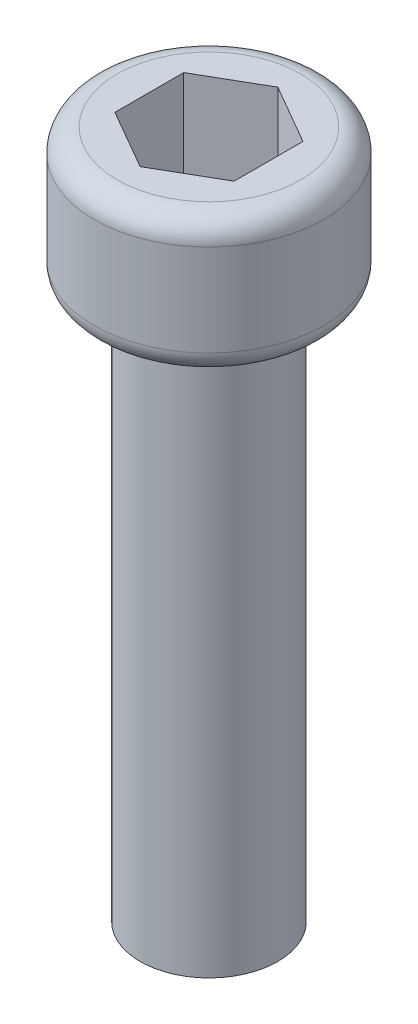
SolidWorks part; units mm, degrees
material "AISI 304"
ref_plane "前视基准面" through (0, 0, 0) normal (0, 0, 1) x (1, 0, 0)
ref_plane "上视基准面" through (0, 0, 0) normal (0, 1, 0) x (1, 0, 0)
ref_plane "右视基准面" through (0, 0, 0) normal (1, 0, 0) x (0, 0, -1)
sketch "草图1" plane through (0, 0, 0) normal (0, 1, 0) x (1, 0, 0)
  circle A0 centre (0, 0) radius 2.5
  dimension "D1" = 5
extrude "凸台-拉伸1" add sketch "草图1" along normal blind 3
sketch "草图2" plane through (0, 3, 0) normal (0, 1, 0) x (1, 0, 0)
  line L0 (0, 2.717) -> (0, -3.1539) construction
  line L2 (0, 1.5) -> (-1.299, 0.75)
  line L3 (-1.299, 0.75) -> (-1.299, -0.75)
  line L4 (-1.299, -0.75) -> (0, -1.5)
  line L5 (0, -1.5) -> (1.299, -0.75)
  line L6 (1.299, -0.75) -> (1.299, 0.75)
  line L7 (1.299, 0.75) -> (0, 1.5)
  circle A0 centre (0, 0) radius 1.299 construction
  dimension "D1" = 3
extrude "切除-拉伸1" cut sketch "草图2" against normal blind 2
sketch "草图3" plane through (0, 0, 0) normal (0, -1, 0) x (1, 0, 0)
  circle A0 centre (0, 0) radius 1.5
  dimension "D1" = 3
extrude "凸台-拉伸2" add sketch "草图3" along normal blind 10
cosmetic thread "装饰螺纹线1" parameters "D2"=2
fillet "圆角1" radius 0.5 2 edges at (0, 0, 2.5) (0, 3, 2.5)
sketch "草图4" plane through (0, -10, 0) normal (0, -1, 0) x (1, 0, 0)
  circle A1 centre (0, 0) radius 1.5
  circle A2 centre (0, 0) radius 1.5
  dimension "D1" = 0
extrude "凸台-拉伸3" add sketch "草图4" along normal blind 2
